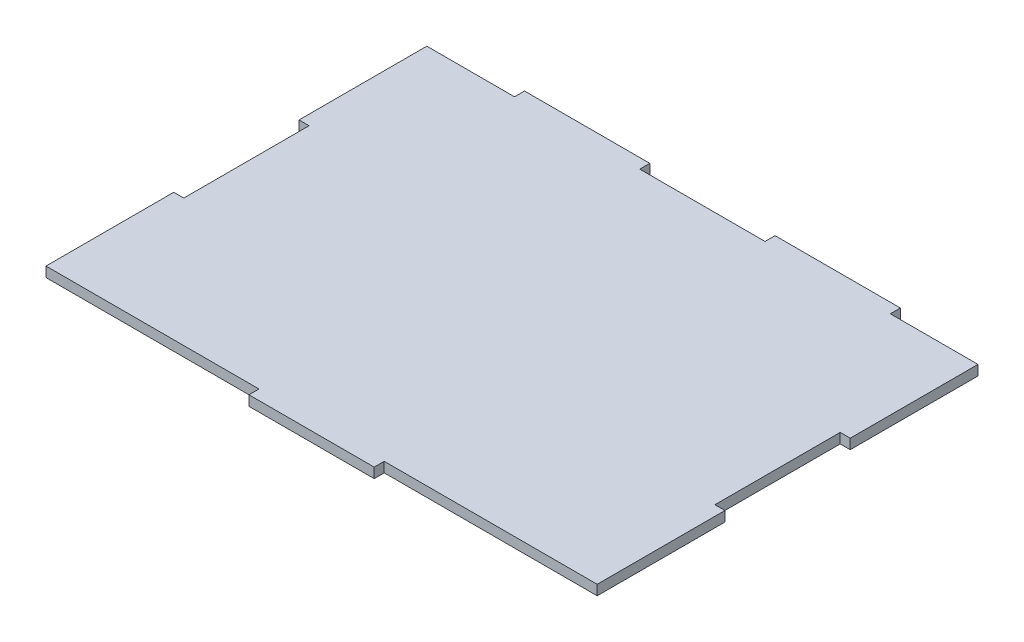
SolidWorks part; units mm, degrees
ref_plane "Front Plane" through (0, 0, 0) normal (0, 0, 1) x (1, 0, 0)
ref_plane "Top Plane" through (0, 0, 0) normal (0, 1, 0) x (1, 0, 0)
ref_plane "Right Plane" through (0, 0, 0) normal (1, 0, 0) x (0, 0, -1)
sketch "Sketch3" plane through (0, 0, 0) normal (0, 1, 0) x (1, 0, 0)
  line L0 (-110, 76) -> (-110, 25)
  line L1 (-25, -80) -> (25, -80)
  line L2 (110, -76) -> (110, -25)
  line L3 (75, 80) -> (25, 80)
  line L4 (-106, -25) -> (-106, 25)
  line L5 (-106, 25) -> (-110, 25)
  line L6 (-106, -25) -> (-110, -25)
  line L7 (0, -55) -> (0, 55) construction
  line L8 (106, 25) -> (110, 25)
  line L9 (106, -25) -> (110, -25)
  line L10 (106, -25) -> (106, 25)
  line L11 (-110, -25) -> (-110, -76)
  line L12 (110, 25) -> (110, 76)
  line L13 (-110, -76) -> (-25, -76)
  line L14 (-25, -76) -> (-25, -80)
  line L15 (25, -76) -> (25, -80)
  line L16 (25, -76) -> (110, -76)
  line L17 (-110, 76) -> (-75, 76)
  line L18 (-75, 80) -> (-75, 76)
  line L19 (-25, 76) -> (-25, 80)
  line L20 (25, 80) -> (25, 76)
  line L21 (75, 80) -> (75, 76)
  line L22 (-25, 76) -> (25, 76)
  line L23 (-25, 80) -> (-75, 80)
  line L24 (75, 76) -> (110, 76)
  point P13 (-108, -25)
  dimension "D1" = 160
  dimension "D2" = 220
  dimension "D3" = 4
  dimension "D4" = 50
  dimension "D5" = 25
  dimension "D6" = 80
  dimension "D7" = 4
  dimension "D8" = 50
  dimension "D9" = 25
  dimension "D10" = 4
  dimension "D11" = 50
  dimension "D12" = 50
  dimension "D13" = 50
  dimension "D14" = 25
extrude "Boss-Extrude1" add sketch "Sketch3" along normal blind 4
